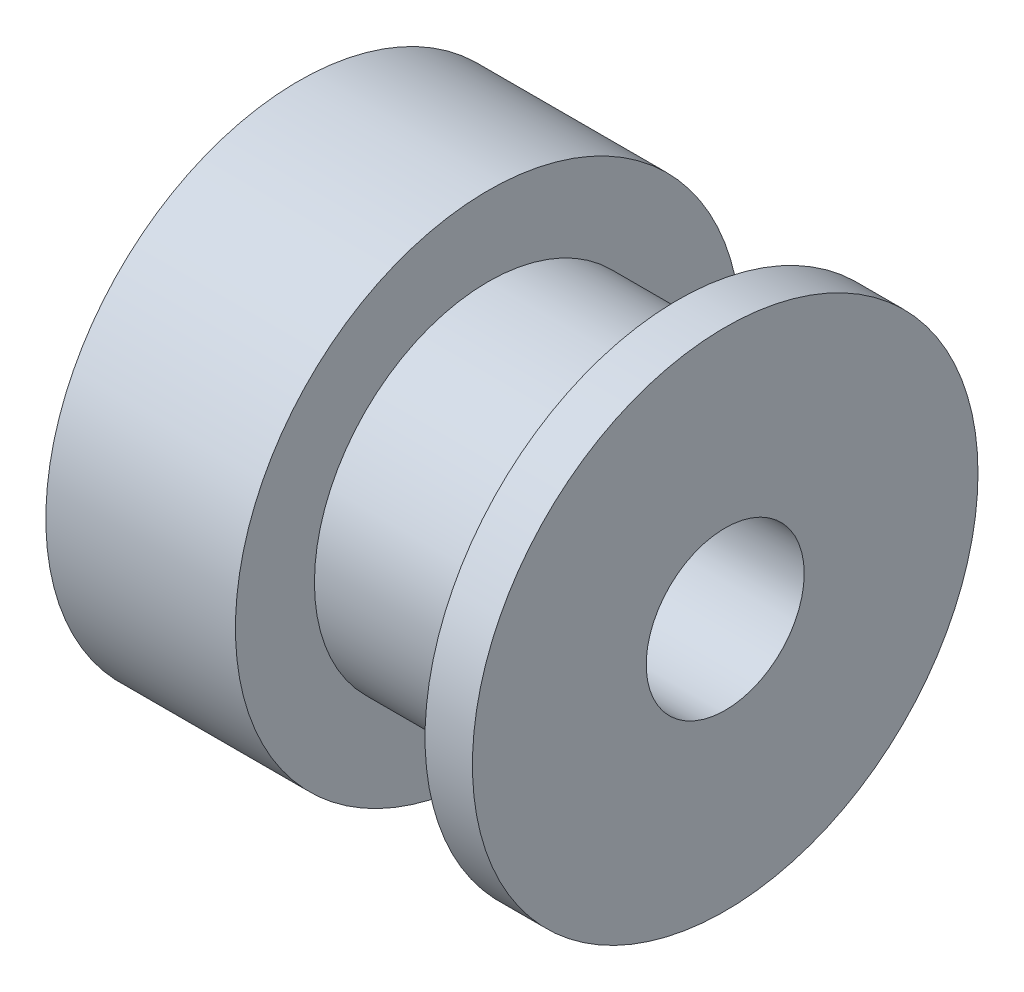
SolidWorks part; units mm, degrees
ref_plane "Front Plane" through (0, 0, 0) normal (0, 0, 1) x (1, 0, 0)
ref_plane "Top Plane" through (0, 0, 0) normal (0, 1, 0) x (1, 0, 0)
ref_plane "Right Plane" through (0, 0, 0) normal (1, 0, 0) x (0, 0, -1)
sketch "Sketch1" plane through (0, 0, 0) normal (1, 0, 0) x (0, 0, -1)
  circle A0 centre (0, 0) radius 2.5
  circle A1 centre (0, 0) radius 8
  dimension "D1" = 5
  dimension "D2" = 16
extrude "Boss-Extrude1" add sketch "Sketch1" along normal blind 6
sketch "Sketch2" plane through (6, 0, 0) normal (1, 0, 0) x (0, 0, -1)
  circle A0 centre (0, 0) radius 2.5
  circle A1 centre (0, 0) radius 5.5
  dimension "D1" = 11
extrude "Boss-Extrude2" add sketch "Sketch2" along normal blind 6
sketch "Sketch3" plane through (12, 0, 0) normal (1, 0, 0) x (0, 0, -1)
  circle A0 centre (0, 0) radius 2.5
  circle A1 centre (0, 0) radius 8
  dimension "D1" = 16
  dimension "D2" = 5
extrude "Boss-Extrude3" add sketch "Sketch3" along normal blind 1.5
